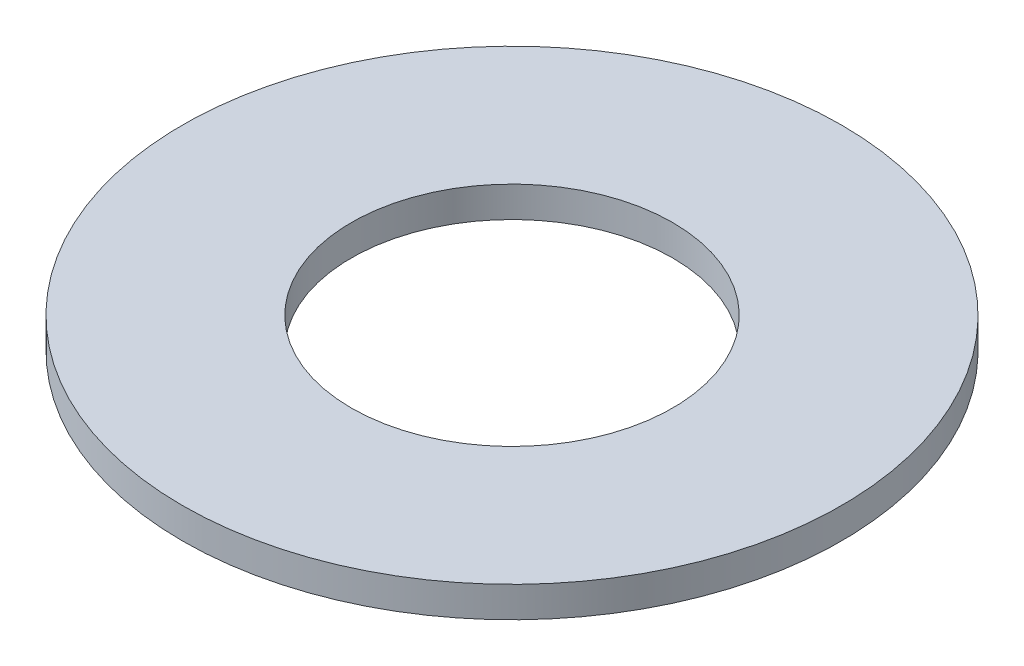
SolidWorks part; units mm, degrees
ref_plane "Front Plane" through (0, 0, 0) normal (0, 0, 1) x (1, 0, 0)
ref_plane "Top Plane" through (0, 0, 0) normal (0, 1, 0) x (1, 0, 0)
ref_plane "Right Plane" through (0, 0, 0) normal (1, 0, 0) x (0, 0, -1)
sketch "Sketch1" plane through (0, 0, 0) normal (0, 1, 0) x (1, 0, 0)
  circle A0 centre (0, 0) radius 15.7
  circle A1 centre (0, 0) radius 32.2
  dimension "D1" = 31.4
  dimension "D2" = 64.4
extrude "Boss-Extrude1" add sketch "Sketch1" along normal blind 3
